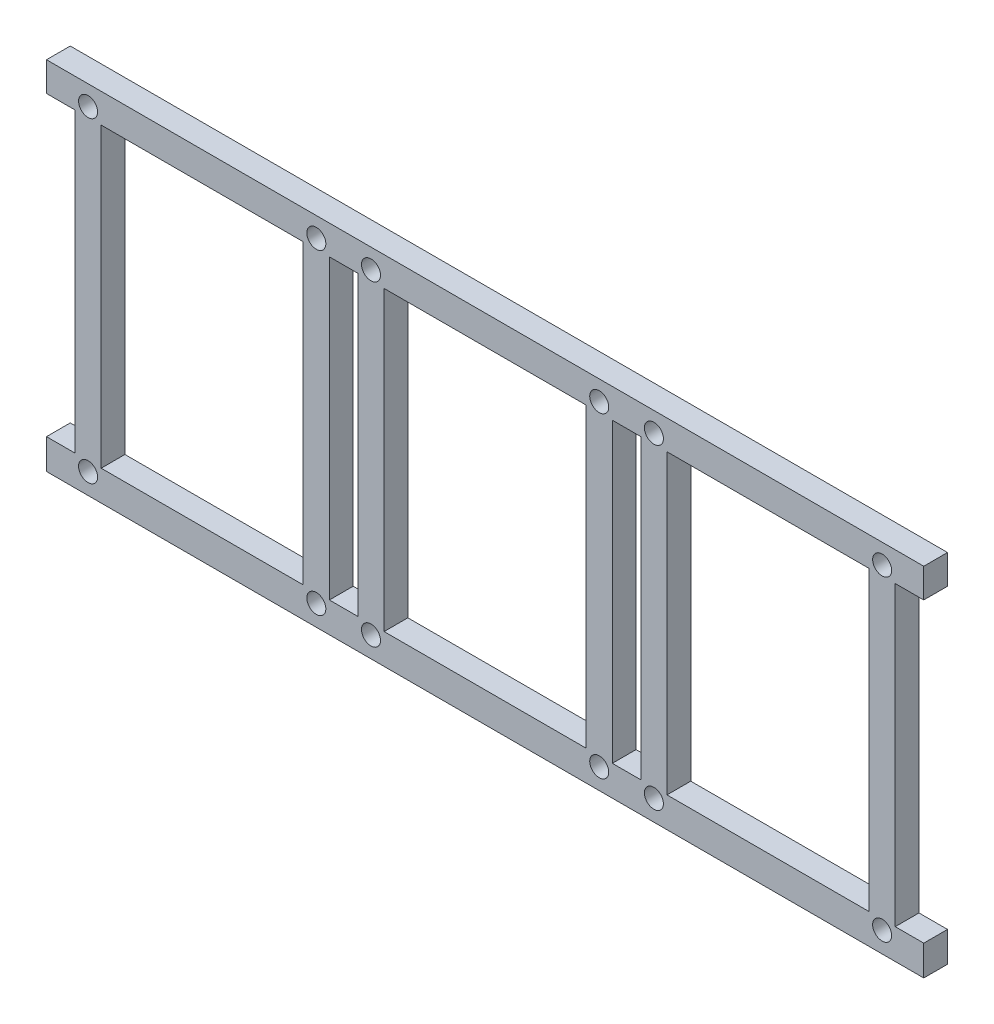
SolidWorks part; units mm, degrees
ref_plane "前视基准面" through (0, 0, 0) normal (0, 0, 1) x (1, 0, 0)
ref_plane "上视基准面" through (0, 0, 0) normal (0, 1, 0) x (1, 0, 0)
ref_plane "右视基准面" through (0, 0, 0) normal (1, 0, 0) x (0, 0, -1)
sketch "草图1" plane through (0, 0, 0) normal (0, 0, 1) x (1, 0, 0)
  line L0 (2093.8771, 1448.6786) -> (1909.3771, 1448.6786)
  line L1 (1909.3771, 1523.6786) -> (2093.8771, 1523.6786)
  line L2 (1968.8771, 1486.2791) -> (1968.8771, 1517.5291)
  line L3 (1968.8771, 1486.2791) -> (1968.8771, 1455.0291)
  line L4 (1974.8771, 1455.0291) -> (1974.8771, 1517.5291)
  line L5 (1968.8771, 1455.0291) -> (1974.8771, 1455.0291)
  line L6 (1974.8771, 1517.5291) -> (1968.8771, 1517.5291)
  line L7 (1980.3771, 1517.5291) -> (1980.3771, 1454.9446)
  line L8 (1980.3771, 1455.0291) -> (2022.8771, 1455.0291)
  line L9 (2028.3771, 1455.0291) -> (2034.3771, 1455.0291)
  line L10 (2039.8771, 1455.0291) -> (2082.3771, 1455.0291)
  line L11 (2087.8771, 1455.0291) -> (2093.8771, 1455.0291)
  line L12 (1980.3771, 1517.5291) -> (2022.8771, 1517.5291)
  line L13 (2028.3771, 1517.5291) -> (2034.3771, 1517.5291)
  line L14 (2039.8771, 1517.5291) -> (2082.3771, 1517.5291)
  line L15 (2087.8771, 1517.5291) -> (2093.8771, 1517.5291)
  line L16 (1963.3771, 1517.5291) -> (1920.8771, 1517.5291)
  line L17 (1915.3771, 1517.5291) -> (1909.3771, 1517.5291)
  line L18 (1963.3771, 1455.0291) -> (1920.8771, 1455.0291)
  line L19 (1915.3771, 1455.0291) -> (1909.3771, 1455.0291)
  line L20 (2022.8771, 1517.5291) -> (2022.8771, 1455.0291)
  line L21 (2028.3771, 1517.5291) -> (2028.3771, 1455.0291)
  line L22 (2034.3771, 1517.5291) -> (2034.3771, 1455.0291)
  line L23 (2039.8771, 1517.5291) -> (2039.8771, 1455.0291)
  line L24 (2082.3771, 1517.5291) -> (2082.3771, 1455.0291)
  line L25 (2087.8771, 1517.5291) -> (2087.8771, 1455.0291)
  line L26 (1920.8771, 1517.5291) -> (1920.8771, 1455.0291)
  line L27 (1915.3771, 1517.5291) -> (1915.3771, 1455.0291)
  line L28 (1963.3771, 1517.5291) -> (1963.3771, 1455.0291)
  line L29 (1915.3771, 1517.5291) -> (1909.3771, 1517.5291)
  line L30 (1909.3771, 1455.0291) -> (1909.3771, 1448.6786)
  line L31 (1909.3771, 1517.5291) -> (1909.3771, 1523.6786)
  line L32 (2087.8771, 1517.5291) -> (2093.8771, 1517.5291)
  line L33 (2093.8771, 1455.0291) -> (2093.8771, 1448.6786)
  line L34 (2093.8771, 1517.5291) -> (2093.8771, 1523.6786)
  circle A0 centre (1918.1271, 1519.5291) radius 2
  circle A1 centre (1966.1271, 1519.5291) radius 2
  circle A2 centre (1977.6271, 1519.5291) radius 2
  circle A3 centre (2025.6271, 1519.5291) radius 2
  circle A4 centre (2037.1271, 1519.5291) radius 2
  circle A5 centre (2085.1271, 1519.5291) radius 2
  circle A6 centre (1918.1271, 1453.0291) radius 2
  circle A7 centre (1966.1271, 1453.0291) radius 2
  circle A8 centre (1977.6271, 1453.0291) radius 2
  circle A9 centre (2025.6271, 1453.0291) radius 2
  circle A10 centre (2037.1271, 1453.0291) radius 2
  circle A11 centre (2085.1271, 1453.0291) radius 2
extrude "凸台-拉伸1" add sketch "草图1" along normal blind 5 contours L15 L34 L1 L31 L17 L27 L19 L30 L0 L33 L11 L25 A11 A10 A9 A8 A7 A6 A5 A4 A3 A2 A1 A0 L16 L28 L18 L26 L14 L24 L10 L23 L13 L22 L9 L21
